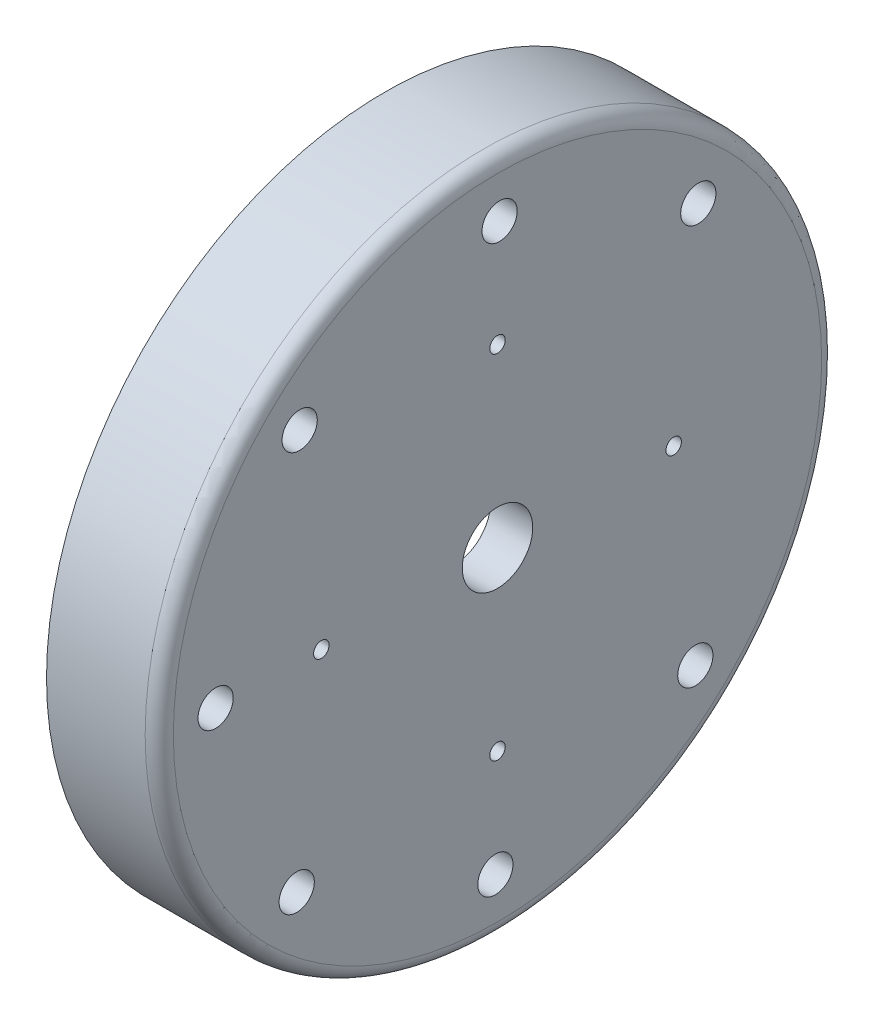
SolidWorks part; units mm, degrees
material "6061 Alloy"
ref_plane "Front Plane" through (0, 0, 0) normal (0, 0, 1) x (1, 0, 0)
ref_plane "Top Plane" through (0, 0, 0) normal (0, 1, 0) x (1, 0, 0)
ref_plane "Right Plane" through (0, 0, 0) normal (1, 0, 0) x (0, 0, -1)
sketch "Sketch1" plane through (0, 0, 0) normal (1, 0, 0) x (0, 0, -1)
  circle A0 centre (0, 0) radius 60.96
extrude "Boss-Extrude1" add sketch "Sketch1" along normal blind 20.32
fillet "Fillet1" radius 2.54 1 edges at (20.32, 0, -60.96)
sketch "Sketch2" plane through (20.32, 0, 0) normal (1, 0, 0) x (0, 0, -1)
  circle A0 centre (0, 0) radius 4.508
extrude "Cut-Extrude1" cut sketch "Sketch2" against normal blind 6.35
sketch "Sketch3" plane through (20.32, 0, 0) normal (1, 0, 0) x (0, 0, -1)
  circle A0 centre (22.5439, 0) radius 3.175
extrude "Cut-Extrude2" [suppressed] cut sketch "Sketch3" against normal blind 19.05
pattern_circular "CirPattern1" [suppressed] count 8 over 360
sketch "Sketch4" plane through (20.32, 0, 0) normal (1, 0, 0) x (0, 0, -1)
  circle A0 centre (0, 0) radius 6.35
  dimension "D1" = 12.7
extrude "Cut-Extrude3" cut sketch "Sketch4" against normal through all
sketch "Sketch5" plane through (0, 0, 0) normal (-1, 0, 0) x (0, 0, 1)
  circle A0 centre (-36.1888, 35.6513) radius 3.175
  dimension "D1" = 50.8
extrude "Cut-Extrude4" cut sketch "Sketch5" against normal through all contours A0
pattern_circular "CirPattern2" count 8 over 360 about axis through (0, 0, 0) along (1, 0, 0) skipping 7 of "Cut-Extrude4"
sketch "Sketch6" plane through (0, 0, 0) normal (-1, 0, 0) x (0, 0, 1)
  circle A0 centre (0, 0) radius 34.925
  dimension "D1" = 69.85
extrude "Cut-Extrude5" cut sketch "Sketch6" against normal offset from surface (12.7 mm away) 7.62 up to face at (20.32, 48.5535, 1.865)
sketch "Sketch7" plane through (12.7, 0, 0) normal (-1, 0, 0) x (0, 0, 1)
  circle A0 centre (0, 0) radius 31.75 construction
  circle A1 centre (0, 31.75) radius 1.397
  circle A2 centre (0, 0) radius 31.75 construction
  circle A3 centre (31.75, 0) radius 1.397
  circle A4 centre (0, 0) radius 31.75 construction
  circle A5 centre (0, -31.75) radius 1.397
  circle A6 centre (0, 0) radius 31.75 construction
  circle A7 centre (-31.75, 0) radius 1.397
  point P17 (0, 0)
  dimension "D1" = 63.5
  dimension "D2" = 2.794
  dimension "D3" = 4
extrude "Cut-Extrude6" cut sketch "Sketch7" against normal up to surface (7.62 mm away) up to face at (20.32, 48.5535, 1.865)
